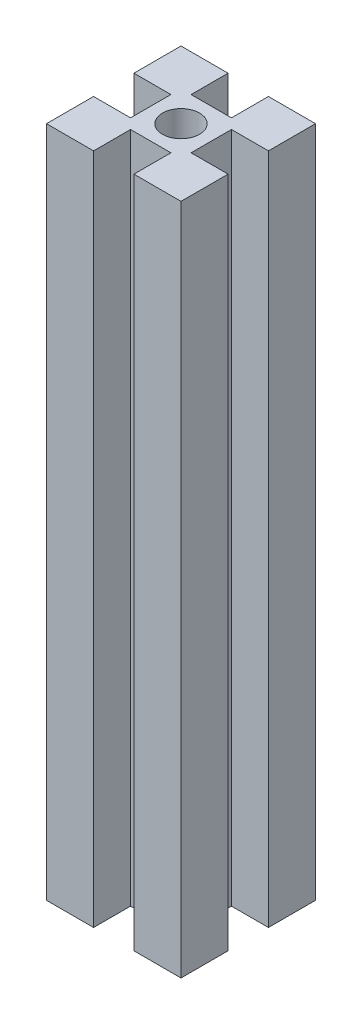
SolidWorks part; units mm, degrees
ref_plane "Front Plane" through (0, 0, 0) normal (0, 0, 1) x (1, 0, 0)
ref_plane "Top Plane" through (0, 0, 0) normal (0, 1, 0) x (1, 0, 0)
ref_plane "Right Plane" through (0, 0, 0) normal (1, 0, 0) x (0, 0, -1)
sketch "Sketch1" plane through (0, 0, 0) normal (0, 1, 0) x (1, 0, 0)
  line L1 (10, -10) -> (-10, -10)
  line L2 (10, -10) -> (10, 10)
  line L3 (10, 10) -> (-10, 10)
  line L4 (-10, -10) -> (-10, 10)
  line L5 (10, -10) -> (-10, 10) construction
  line L6 (10, 10) -> (-10, -10) construction
  point P0 (0, 0)
  dimension "D1" = 20
  dimension "D2" = 20
extrude "Body" add sketch "Sketch1" along normal blind 100
sketch "Sketch2" plane through (0, 100, 0) normal (0, 1, 0) x (1, 0, 0)
  line L0 (10, 10) -> (-10, 10) construction
  line L1 (-3, 10) -> (3, 10)
  line L2 (-3, 10) -> (-3, 4.5)
  line L3 (-3, 4.5) -> (3, 4.5)
  line L4 (3, 10) -> (3, 4.5)
  line L5 (10, 3) -> (10, -3)
  line L6 (10, 3) -> (4.5, 3)
  line L7 (4.5, 3) -> (4.5, -3)
  line L8 (10, -3) -> (4.5, -3)
  line L9 (3, -10) -> (-3, -10)
  line L10 (3, -10) -> (3, -4.5)
  line L11 (3, -4.5) -> (-3, -4.5)
  line L12 (-3, -10) -> (-3, -4.5)
  line L13 (-10, -3) -> (-10, 3)
  line L14 (-10, -3) -> (-4.5, -3)
  line L15 (-4.5, -3) -> (-4.5, 3)
  line L16 (-10, 3) -> (-4.5, 3)
  circle A0 centre (0, 0) radius 2.75
  point P10 (0, 4.5)
  point P25 (0, 0)
  dimension "D1" = 5.5
  dimension "D2" = 5.5
  dimension "D3" = 6
  dimension "D4" = 4
extrude "Profil" cut sketch "Sketch2" against normal through all
